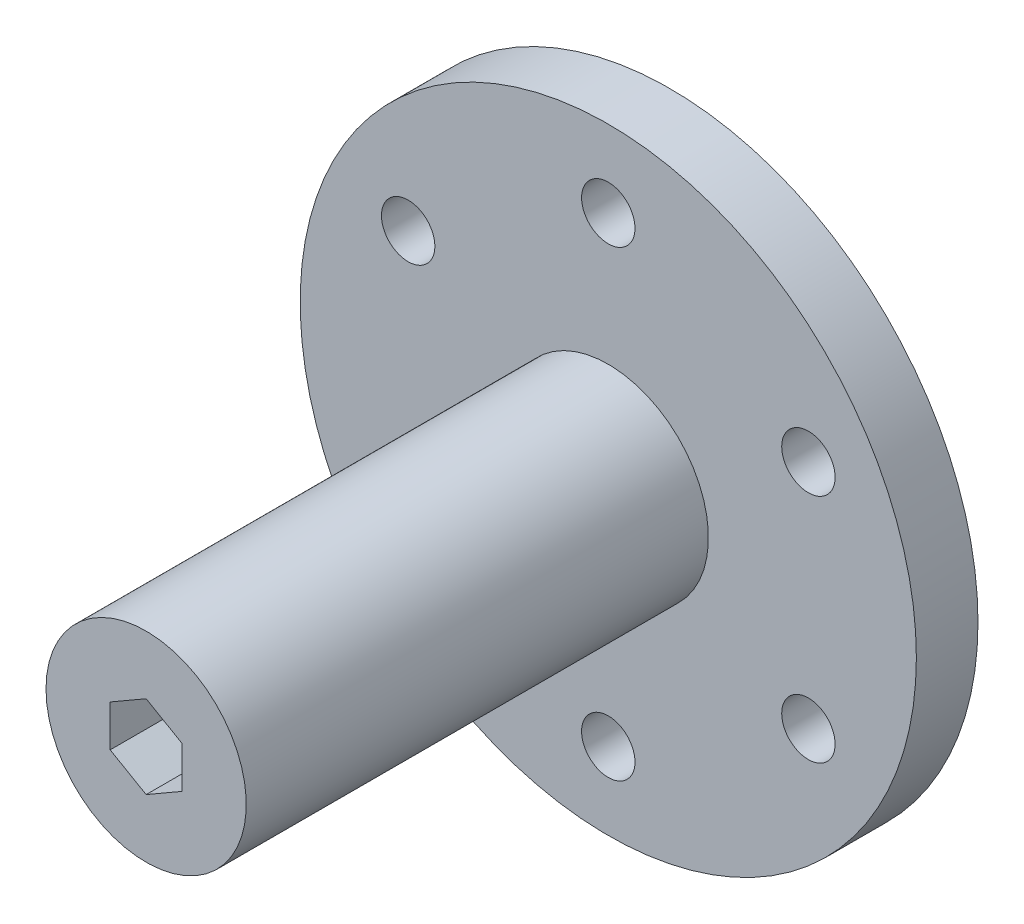
SolidWorks part; units mm, degrees
ref_plane "Front Plane" through (0, 0, 0) normal (0, 0, 1) x (1, 0, 0)
ref_plane "Top Plane" through (0, 0, 0) normal (0, 1, 0) x (1, 0, 0)
ref_plane "Right Plane" through (0, 0, 0) normal (1, 0, 0) x (0, 0, -1)
sketch "Sketch1" plane through (0, 0, 0) normal (0, 0, 1) x (1, 0, 0)
  circle A0 centre (0, 0) radius 30
  dimension "D1" = 60
extrude "Boss-Extrude1" add sketch "Sketch1" along normal blind 6
sketch "Sketch2" plane through (0, 0, 6) normal (0, 0, 1) x (1, 0, 0)
  circle A0 centre (0, 0) radius 9.75
  dimension "D1" = 19.5
extrude "Boss-Extrude2" add sketch "Sketch2" along normal blind 45
sketch "Sketch3" plane through (0, 0, 51) normal (0, 0, 1) x (1, 0, 0)
  line L1 (0, 4.0415) -> (-3.5, 2.0207)
  line L2 (-3.5, 2.0207) -> (-3.5, -2.0207)
  line L3 (-3.5, -2.0207) -> (0, -4.0415)
  line L4 (0, -4.0415) -> (3.5, -2.0207)
  line L5 (3.5, -2.0207) -> (3.5, 2.0207)
  line L6 (3.5, 2.0207) -> (0, 4.0415)
  circle A0 centre (0, 0) radius 3.5 construction
  dimension "D1" = 7
extrude "Cut-Extrude1" cut sketch "Sketch3" against normal through all
sketch "Sketch5" plane through (0, 0, 0) normal (0, 0, -1) x (-1, 0, 0)
  circle A0 centre (0, 22.5) radius 2.6
  circle A1 centre (19.4856, 11.25) radius 2.6
  circle A2 centre (19.4856, -11.25) radius 2.6
  circle A3 centre (0, -22.5) radius 2.6
  circle A4 centre (-19.4856, -11.25) radius 2.6
  circle A5 centre (-19.4856, 11.25) radius 2.6
  point P15 (0, 0)
  dimension "D1" = 5.2
  dimension "D2" = 22.5
  dimension "D3" = 6
extrude "Cut-Extrude3" cut sketch "Sketch5" against normal blind 30
